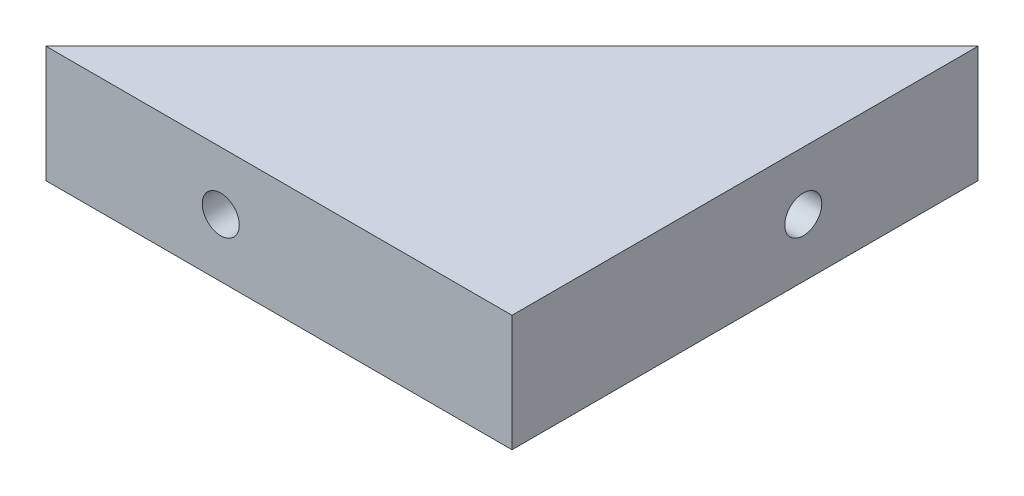
SolidWorks part; units mm, degrees
ref_plane "Front Plane" through (0, 0, 0) normal (0, 0, 1) x (1, 0, 0)
ref_plane "Top Plane" through (0, 0, 0) normal (0, 1, 0) x (1, 0, 0)
ref_plane "Right Plane" through (0, 0, 0) normal (1, 0, 0) x (0, 0, -1)
sketch "Sketch1" plane through (0, 0, 0) normal (0, 1, 0) x (1, 0, 0)
  line L0 (-25.4, -25.4) -> (25.4, 25.4)
  line L1 (-25.4, -25.4) -> (25.4, -25.4)
  line L4 (25.4, -25.4) -> (25.4, 25.4)
  line L5 (-25.4, -25.4) -> (25.4, 25.4) construction
  line L6 (0, 0) -> (25.4, -25.4) construction
  point P0 (0, 0)
  dimension "D1" = 50.8
  dimension "D2" = 50.8
extrude "Boss-Extrude1" add sketch "Sketch1" along normal blind 12.7
hole_wizard "#10-32 Tapped Hole1" positions "Sketch3" profile "Sketch2" tap size "#10-32" standard "ANSI Inch"
sketch "Sketch3" plane through (25.4, 0, 0) normal (1, 0, 0) x (0, 0, -1)
  line L0 (-25.4, 12.7) -> (-25.4, 0) construction
  line L1 (-25.4, 0) -> (25.4, 0) construction
  point P0 (6.35, 6.35)
  dimension "D1" = 31.75
  dimension "D2" = 6.35
sketch "Sketch2" plane through (25.4, 6.35, -6.35) normal (0, 1, 0) x (0, 0, -1)
  line L0 (0, 0) -> (0, 26.6133)
  line L1 (0, 26.6133) -> (2.0193, 25.4)
  line L2 (2.0193, 25.4) -> (2.0193, 0)
  line L5 (2.0193, 0) -> (0, 0)
  line L10 (0, 26.6133) -> (-2.0193, 25.4) construction
  line L11 (0, -6.35) -> (0, 107.95) construction
  dimension "Tap Drill Dia." = 4.0386
  dimension "Tap Drill Depth" = 25.4
  dimension "Drill Angle" = 118
hole_wizard "#10-32 Tapped Hole2" positions "Sketch5" profile "Sketch4" tap size "#10-32" standard "ANSI Inch"
sketch "Sketch5" plane through (0, 0, 25.4) normal (0, 0, 1) x (1, 0, 0)
  line L0 (25.4, 12.7) -> (25.4, 0) construction
  line L2 (-25.4, 12.7) -> (25.4, 12.7) construction
  point P0 (-6.35, 6.35)
  point P9 (-66.9276, 27.8397)
  point P16 (-9.7659, 12.7)
  dimension "D1" = 31.75
  dimension "D2" = 6.35
sketch "Sketch4" plane through (-6.35, 6.35, 25.4) normal (1, 0, 0) x (0, -1, 0)
  line L0 (0, 0) -> (0, 26.6133)
  line L1 (0, 26.6133) -> (2.0193, 25.4)
  line L2 (2.0193, 25.4) -> (2.0193, 0)
  line L5 (2.0193, 0) -> (0, 0)
  line L10 (0, 26.6133) -> (-2.0193, 25.4) construction
  line L11 (0, -6.35) -> (0, 107.95) construction
  dimension "Tap Drill Dia." = 4.0386
  dimension "Tap Drill Depth" = 25.4
  dimension "Drill Angle" = 118
